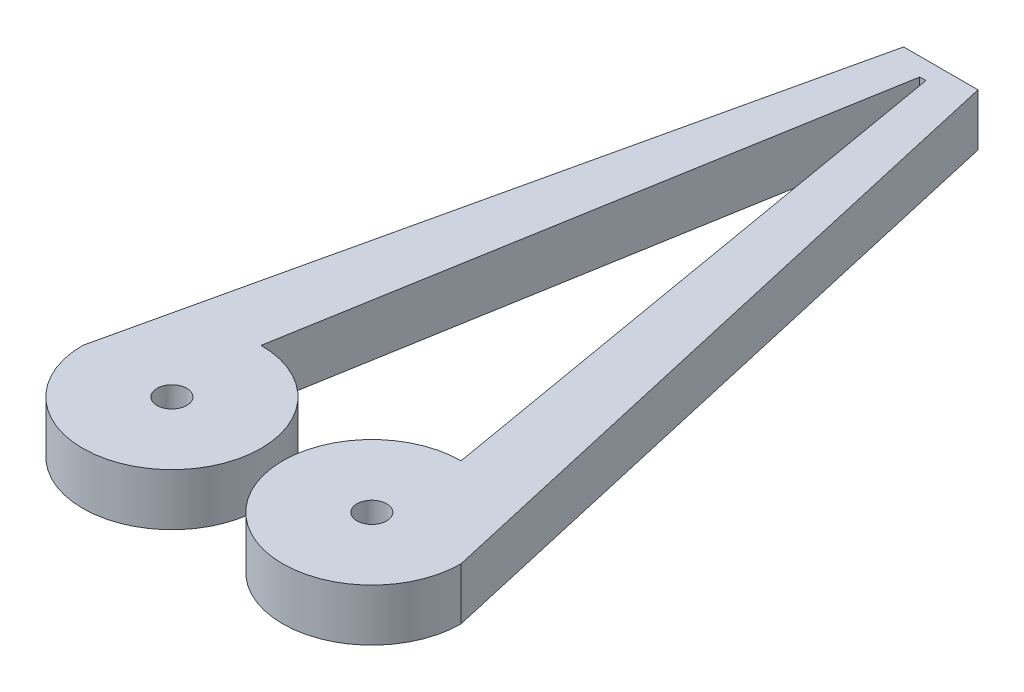
SolidWorks part; units mm, degrees
ref_plane "Front Plane" through (0, 0, 0) normal (0, 0, 1) x (1, 0, 0)
ref_plane "Top Plane" through (0, 0, 0) normal (0, 1, 0) x (1, 0, 0)
ref_plane "Right Plane" through (0, 0, 0) normal (1, 0, 0) x (0, 0, -1)
sketch "Sketch1" plane through (0, 0, 0) normal (0, 1, 0) x (1, 0, 0)
  line L0 (13.0326, 87.5796) -> (13.8674, 87.5796)
  line L2 (13.45, 90) -> (18.45, 90)
  line L3 (13.45, 90) -> (8.45, 90)
  line L4 (8.45, 90) -> (-12, 0)
  line L5 (18.45, 90) -> (38.9, 0)
  line L6 (0, -12) -> (26.9, -12)
  line L7 (13.0326, 87.5796) -> (0, 12)
  line L8 (13.8674, 87.5796) -> (26.9, 12)
  circle A0 centre (0, 0) radius 2
  circle A1 centre (26.9, 0) radius 2
  arc A2 (-12, 0) -> (0, 12) centre (0, 0) ccw
  arc A3 (26.9, 12) -> (38.9, 0) centre (26.9, 0) ccw
extrude "Boss-Extrude1" add sketch "Sketch1" along normal blind 7 contours A2 L7 L3 L4 A0 | A3 L5 L2 L8 A1
sketch "Sketch3" plane through (0, 0, -90) normal (0, 0, -1) x (-1, 0, 0)
  point P4 (-13.45, 3.5)
